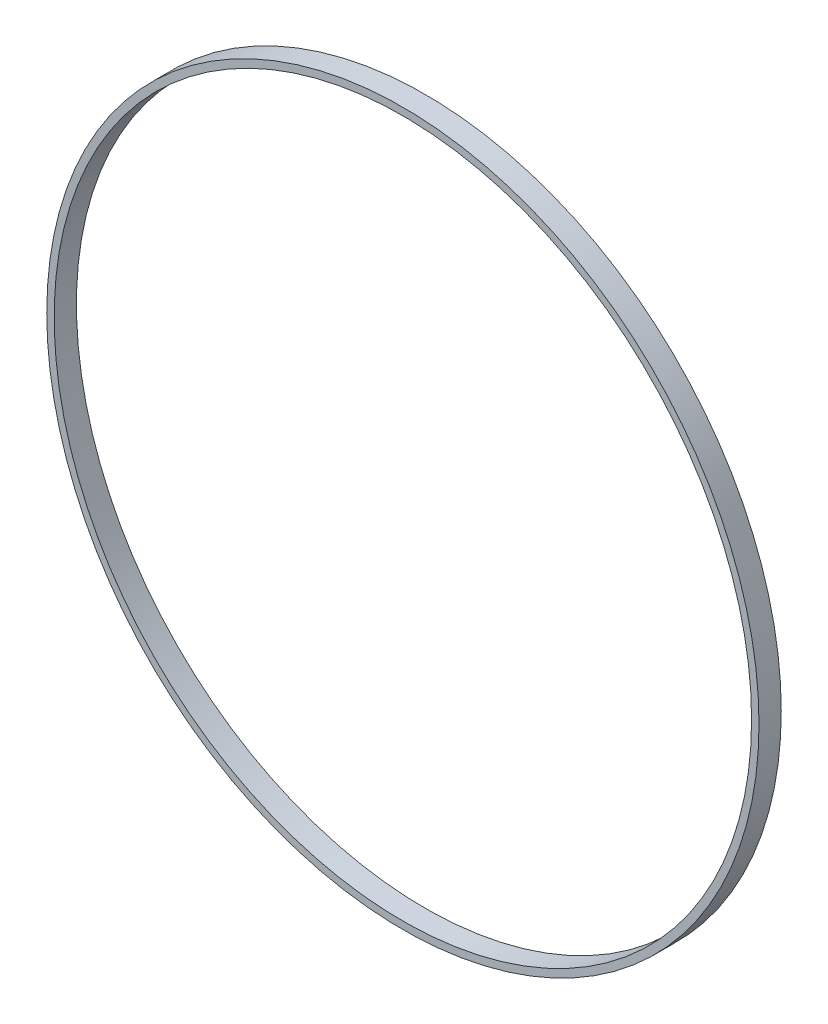
SolidWorks part; units mm, degrees
ref_plane "Front Plane" through (0, 0, 0) normal (0, 0, 1) x (1, 0, 0)
ref_plane "Top Plane" through (0, 0, 0) normal (0, 1, 0) x (1, 0, 0)
ref_plane "Right Plane" through (0, 0, 0) normal (1, 0, 0) x (0, 0, -1)
sketch "Sketch1" plane through (0, 0, 0) normal (0, 0, 1) x (1, 0, 0)
  circle A0 centre (0, 0) radius 120
  circle A1 centre (0, 0) radius 117.5
  dimension "D1" = 240
  dimension "D2" = 235
extrude "Boss-Extrude1" add sketch "Sketch1" along normal blind 7.5
